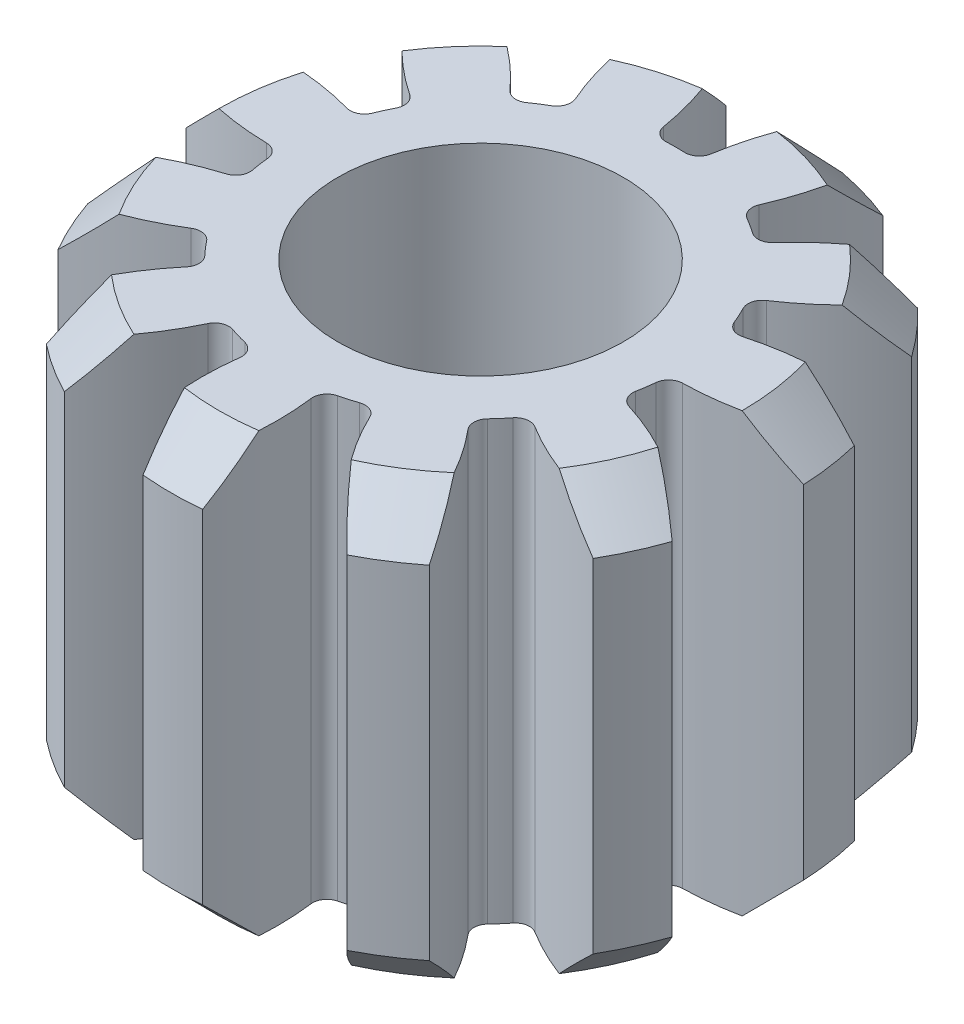
SolidWorks part; units mm, degrees
ref_plane "Front Plane" through (0, 0, 0) normal (0, 0, 1) x (1, 0, 0)
ref_plane "Top Plane" through (0, 0, 0) normal (0, 1, 0) x (1, 0, 0)
ref_plane "Right Plane" through (0, 0, 0) normal (1, 0, 0) x (0, 0, -1)
sketch "Sketch1" plane through (0, 0, 0) normal (0, 1, 0) x (1, 0, 0)
  circle A0 centre (0, 0) radius 1.375 construction
  circle A1 centre (0, 0) radius 1.625
  dimension "D1" = 2.75
  dimension "D2" = 3.25
extrude "Boss-Extrude1" add sketch "Sketch1" along normal blind 2.3
sketch "Sketch2" plane through (0, 2.3, 0) normal (0, 1, 0) x (1, 0, 0)
  line L0 (0, 0) -> (0, 1.625) construction
  line L1 (0, 0) -> (0.8785, 1.367) construction
  line L2 (0, 0) -> (0.4578, 1.5592) construction
  line L3 (-0.1152, 1.0185) -> (0, 0) construction
  line L4 (-0.1957, 1.361) -> (0.1957, 1.361) construction
  line L5 (0.1957, 1.361) -> (0.5712, 1.2507) construction
  line L6 (-0.2827, 1.6002) -> (0, 0.8234) construction
  circle A0 centre (0, 0) radius 1.125 construction
  circle A2 centre (0, 0) radius 1.625 construction
  arc A3 (-0.1152, 1.0185) -> (-0.3052, 1.5961) centre (-1.5972, 0.8509) ccw
  arc A4 (0.1152, 1.0185) -> (0.3052, 1.5961) centre (1.5972, 0.8509) cw
  circle A5 centre (0, 0) radius 1.375 construction
  arc A7 (0.1152, 1.0185) -> (-0.1152, 1.0185) centre (0, 0) ccw
  arc A8 (0.3052, 1.5961) -> (-0.3052, 1.5961) centre (0, 0) ccw
  dimension "D1" = 32.727
  dimension "D2" = 0.5
  dimension "D4" = 20
extrude "Cut-Extrude1" cut sketch "Sketch2" against normal through all
fillet "Fillet1" radius 0.075 2 edges at (0.1152, 1.15, -1.0185) (-0.1152, 1.15, -1.0185)
chamfer "Chamfer1" distance 0.25 2 edges at (0, 0, 1.625) (0, 2.3, 1.625)
pattern_circular "CirPattern2" count 11 over 360 about axis through (0, 0, 0) along (0, 1, 0) of "Cut-Extrude1", "Fillet1"
sketch "Sketch3" plane through (0, 2.3, 0) normal (0, 1, 0) x (1, 0, 0)
  circle A0 centre (0, 0) radius 0.75
  dimension "D1" = 1.5
extrude "Cut-Extrude2" cut sketch "Sketch3" against normal through all
equation "\"Module of gear\"= 0.25"
equation "\"Number of teeth\"= 11"
equation "\"Pressure Angle\"= 20"
equation "\"D1@Sketch1\"=\"Module of gear\" * \"Number of teeth\""
equation "\"D2@Sketch1\"=(\"Number of teeth\" + 2) * \"Module of gear\""
equation "\"D1@Sketch2\"=360 / \"Number of teeth\""
equation "\"D2@Sketch2\"=\"Module of gear\" * 2"
equation "\"D4@Sketch2\"=\"Pressure Angle\""
equation "\"D1@Fillet1\"=0.3 * \"Module of gear\""
equation "\"D1@Chamfer1\"=\"Module of gear\""
equation "\"D1@CirPattern2\"=\"Number of teeth\""
